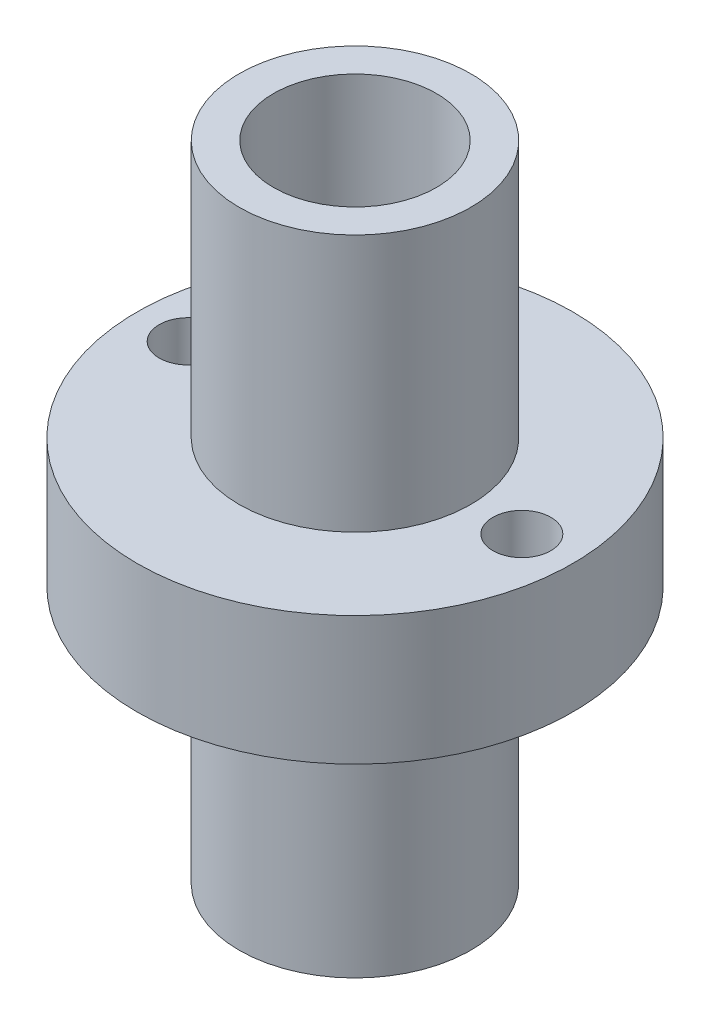
SolidWorks part; units mm, degrees
ref_plane "Alzado" through (0, 0, 0) normal (0, 0, 1) x (1, 0, 0)
ref_plane "Planta" through (0, 0, 0) normal (0, 1, 0) x (1, 0, 0)
ref_plane "Vista lateral" through (0, 0, 0) normal (1, 0, 0) x (0, 0, -1)
sketch "Croquis2" plane through (0, 0, 0) normal (0, 0, 1) x (1, 0, 0)
  line L0 (9.5, 37.5) -> (9.5, -37.5)
  line L1 (25.4, -7.5) -> (13.5, -7.5)
  line L2 (25.4, -7.5) -> (25.4, 7.5)
  line L3 (25.4, 7.5) -> (13.5, 7.5)
  line L4 (13.5, 7.5) -> (13.5, 37.5)
  line L5 (13.5, 37.5) -> (9.5, 37.5)
  line L6 (0, 0) -> (0, -50000) construction
  line L7 (13.5, -7.5) -> (13.5, -37.5)
  line L8 (13.5, -37.5) -> (9.5, -37.5)
  point P9 (9.5, 0)
  dimension "D1" = 9.5
  dimension "D2" = 30
  dimension "D3" = 15
  dimension "D4" = 4
  dimension "D5" = 25.4
  dimension "D6" = 11.9
  dimension "D7" = 30
  dimension "D8" = 75
revolve "Revolución1" add sketch "Croquis2" angle 360 about L6
hole_wizard "Taladro de margen para 1/41" positions "Croquis3" profile "Croquis4" hole size "1/4" standard "Ansi Inch" end condition through all
sketch "Croquis3" plane through (0, 7.5, 0) normal (0, 1, 0) x (1, 0, 0)
  line L0 (0, 0) -> (0, 50000) construction
  line L1 (13.5, 0) -> (25.4, 0) construction
  circle A2 centre (0, 0) radius 25.4 construction
  circle A3 centre (0, 0) radius 13.5 construction
  point P0 (19.45, 0)
  point P2 (-19.45, 0)
  point P25 (19.45, 0)
sketch "Croquis4" plane through (19.45, 7.5, 0) normal (1, 0, 0) x (0, 0, 1)
  line L0 (0, 0) -> (0, 45)
  line L1 (0, 45) -> (3.3782, 45)
  line L2 (3.3782, 45) -> (3.3782, 0)
  line L5 (3.3782, 0) -> (0, 0)
  line L11 (0, -6.35) -> (0, 107.95) construction
  dimension "Diámetro de taladro hasta el siguiente" = 6.7564
  dimension "Profundidad de taladro hasta el siguiente" = 45
